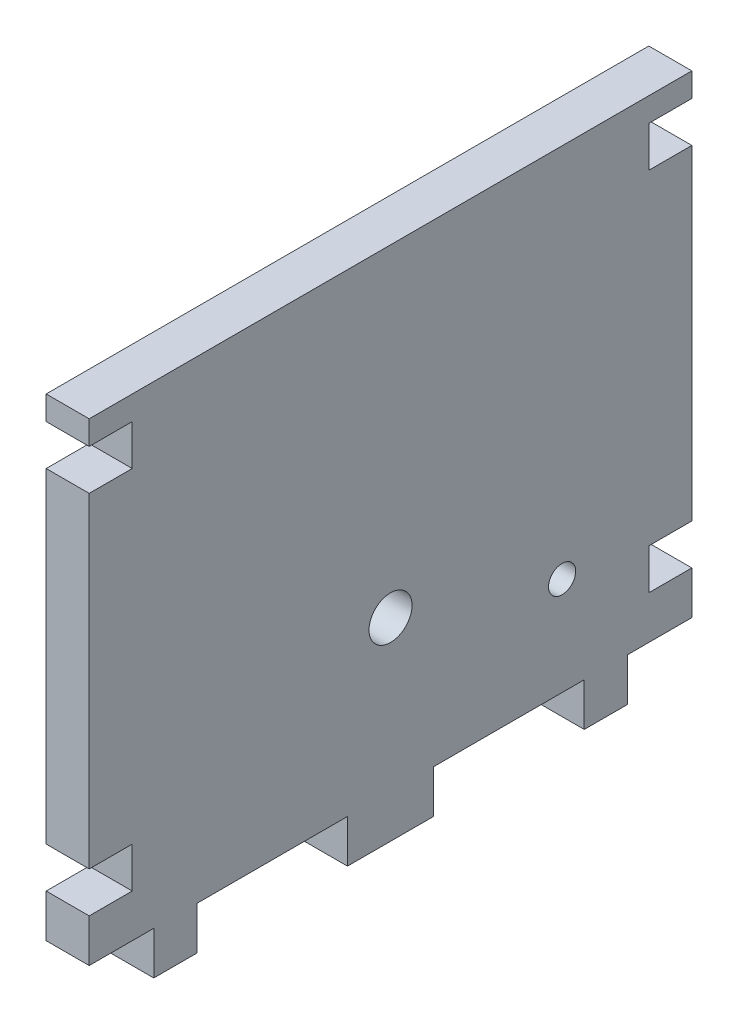
SolidWorks part; units mm, degrees
ref_plane "Front Plane" through (0, 0, 0) normal (0, 0, 1) x (1, 0, 0)
ref_plane "Top Plane" through (0, 0, 0) normal (0, 1, 0) x (1, 0, 0)
ref_plane "Right Plane" through (0, 0, 0) normal (1, 0, 0) x (0, 0, -1)
sketch "Sketch1" plane through (0, 0, 0) normal (1, 0, 0) x (0, 0, -1)
  line L0 (28.575, -28.575) -> (28.575, -22.225)
  line L1 (44.45, -22.225) -> (-44.45, -22.225)
  line L2 (44.45, -22.225) -> (44.45, 22.225)
  line L3 (44.45, 22.225) -> (-44.45, 22.225)
  line L4 (-44.45, -22.225) -> (-44.45, 22.225)
  line L5 (0, 22.225) -> (0, -22.225) construction
  line L6 (44.45, 0) -> (-44.45, 0) construction
  line L7 (6.35, -28.575) -> (-6.35, -28.575)
  line L8 (6.35, -28.575) -> (6.35, -22.225)
  line L9 (6.35, -22.225) -> (-6.35, -22.225)
  line L10 (-6.35, -28.575) -> (-6.35, -22.225)
  line L11 (0, -22.225) -> (0, -28.575) construction
  line L12 (6.35, -25.4) -> (-6.35, -25.4) construction
  line L13 (-28.575, -28.575) -> (-34.925, -28.575)
  line L14 (-28.575, -28.575) -> (-28.575, -22.225)
  line L15 (-28.575, -22.225) -> (-34.925, -22.225)
  line L16 (-34.925, -28.575) -> (-34.925, -22.225)
  line L17 (-31.75, -22.225) -> (-31.75, -28.575) construction
  line L18 (-28.575, -25.4) -> (-34.925, -25.4) construction
  line L19 (28.575, -22.225) -> (34.925, -22.225)
  line L20 (34.925, -28.575) -> (34.925, -22.225)
  line L21 (28.575, -28.575) -> (34.925, -28.575)
  line L22 (-44.45, 47.625) -> (44.45, 47.625)
  line L23 (38.1, -15.875) -> (38.1, -9.8806)
  line L24 (38.1, -9.8806) -> (44.45, -9.8806)
  line L25 (-44.45, -9.8806) -> (-38.1, -9.8806)
  line L26 (-38.1, -9.8806) -> (-38.1, -15.875)
  line L27 (-44.45, 47.625) -> (-44.45, 22.225)
  line L28 (-44.45, 22.225) -> (-43.6191, 22.0477)
  line L29 (44.45, 47.625) -> (44.45, 22.225)
  line L30 (38.1, -15.875) -> (44.45, -15.875)
  line L31 (-38.1, -15.875) -> (-44.45, -15.875)
  line L33 (44.45, 44.0944) -> (38.1, 44.0944)
  line L34 (44.45, 44.0944) -> (44.45, 38.1)
  line L35 (44.45, 38.1) -> (38.1, 38.1)
  line L36 (38.1, 44.0944) -> (38.1, 38.1)
  line L37 (-44.45, 44.0944) -> (-38.1, 44.0944)
  line L38 (-44.45, 44.0944) -> (-44.45, 38.1)
  line L39 (-44.45, 38.1) -> (-38.1, 38.1)
  line L40 (-38.1, 44.0944) -> (-38.1, 38.1)
  circle A0 centre (0, 0) radius 3.175
  circle A1 centre (25.3091, -7.7249) radius 2
  point P0 (0, 0)
  point P4 (0, -25.4)
  point P8 (-31.75, -25.4)
  dimension "D7" = 6.35
  dimension "D8" = 4
  dimension "D1" = 6.35
  dimension "D2" = 6.35
  dimension "D3" = 12.7
  dimension "D4" = 57.15
  dimension "D5" = 44.45
  dimension "D6" = 88.9
  dimension "D9" = 25.3091
  dimension "D10" = 7.7249
  dimension "D11" = 69.85
  dimension "D12" = 5.9944
  dimension "D13" = 6.35
  dimension "D14" = 6.35
  dimension "D15" = 15.875
  dimension "D16" = 5.9944
  dimension "D17" = 6.35
extrude "Boss-Extrude1" add sketch "Sketch1" along normal blind 6.35 contours L4 L1 L2 L3 A1 A0 | L0 L21 L20 L1 | L10 L7 L8 L1 | L16 L13 L14 L1 | L29 L22 L27 L3
sketch "Sketch2" plane through (6.35, 0, 0) normal (1, 0, 0) x (0, 0, -1)
  line L0 (-44.45, -22.225) -> (-44.45, -15.875) construction
  line L1 (-38.1, -9.525) -> (-44.45, -9.525)
  line L2 (-38.1, -9.525) -> (-38.1, 3.175)
  line L3 (-38.1, 3.175) -> (-44.45, 3.175)
  line L4 (-44.45, -9.525) -> (-44.45, 3.175)
  line L5 (-41.275, 3.175) -> (-41.275, -9.525) construction
  line L6 (-38.1, -3.175) -> (-44.45, -3.175) construction
  line L7 (-34.925, -22.225) -> (-44.45, -22.225) construction
  line L8 (0, 0) -> (0, 19.6541) construction
  line L9 (38.1, -9.525) -> (44.45, -9.525)
  line L10 (44.45, -9.525) -> (44.45, 3.175)
  line L11 (38.1, 3.175) -> (44.45, 3.175)
  line L12 (38.1, -9.525) -> (38.1, 3.175)
  point P0 (-41.275, -3.175)
  dimension "D1" = 6.35
  dimension "D2" = 12.7
  dimension "D3" = 12.7
extrude "Cut-Extrude1" [suppressed] cut sketch "Sketch2" against normal blind 6.35
equation "\"D2@Sketch1\"=.25"
equation "\"D3@Sketch1\"=.5"
